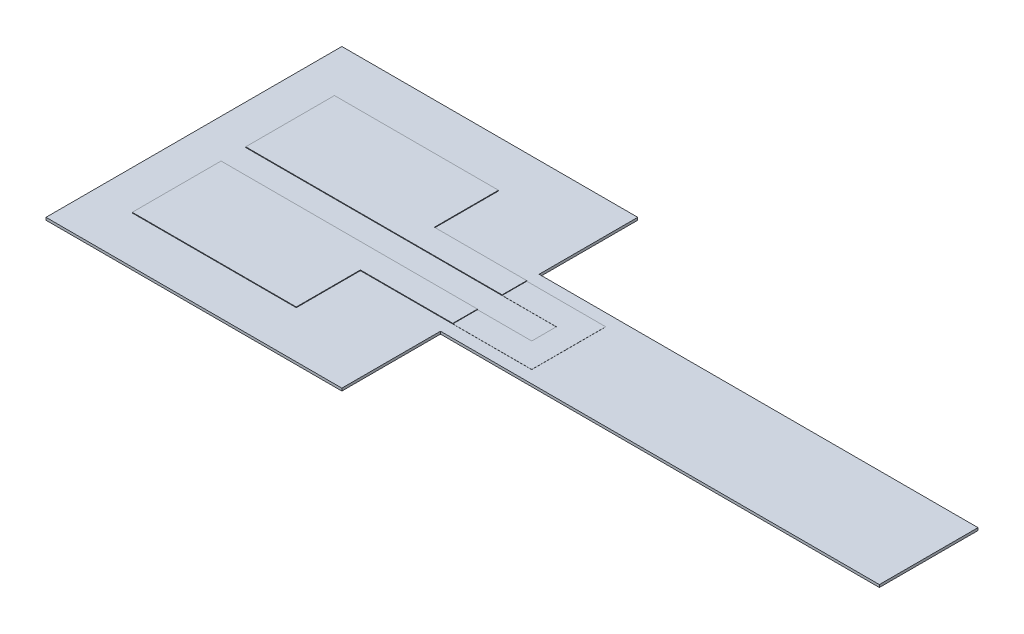
SolidWorks part; units mm, degrees
ref_plane "Front Plane" through (0, 0, 0) normal (0, 0, 1) x (1, 0, 0)
ref_plane "Top Plane" through (0, 0, 0) normal (0, 1, 0) x (1, 0, 0)
ref_plane "Right Plane" through (0, 0, 0) normal (1, 0, 0) x (0, 0, -1)
sketch "Sketch1" plane through (0, 0, 0) normal (0, 1, 0) x (1, 0, 0)
  line L2 (0, -15) -> (30, -15)
  line L3 (30, -15) -> (30, -5)
  line L4 (30, -5) -> (74.5, -5)
  line L5 (74.5, 5) -> (74.5, -5)
  line L6 (0, 15) -> (30, 15)
  line L7 (30, 15) -> (30, 5)
  line L8 (30, 5) -> (74.5, 5)
  line L9 (0, 15) -> (0, -15)
  line L10 (0, 0) -> (74.5, 0) construction
  dimension "D1" = 30
  dimension "D2" = 30
  dimension "D3" = 30
  dimension "D4" = 10
  dimension "D5" = 10
  dimension "D6" = 44.5
  dimension "D7" = 5
extrude "Boss-Extrude1" add sketch "Sketch1" against normal blind 0.26 and the other way blind 0.0001
sketch "Sketch3" plane through (0, 0.0001, 0) normal (0, 1, 0) x (1, 0, 0)
  line L0 (30, 5) -> (30, -5) construction
  line L1 (74.5, 0) -> (30, 0) construction
  line L2 (74.5, -5) -> (74.5, 5) construction
  line L3 (30, 3.75) -> (30, 1.25)
  line L4 (30, 1.25) -> (35.5, 1.25)
  line L5 (35.5, 1.25) -> (35.5, -1.25)
  line L6 (35.5, -1.25) -> (30, -1.25)
  line L7 (30, -1.25) -> (30, -3.75)
  line L8 (30, -3.75) -> (38, -3.75)
  line L9 (38, -3.75) -> (38, 3.75)
  line L10 (38, 3.75) -> (30, 3.75)
  dimension "D1" = 7.5
  dimension "D2" = 8
  dimension "D3" = 2.5
  dimension "D4" = 2.5
  dimension "D5" = 1.25
  dimension "D6" = 2.5
extrude "Boss-Extrude2" add sketch "Sketch3" along normal blind 0.0126 contours L10 L3 L4 L5 L6 L7 L8 L9
sketch "Sketch4" plane through (0, 0.0001, 0) normal (0, 1, 0) x (1, 0, 0)
  line L0 (4, 10.25) -> (4, 1.25)
  line L1 (30, 3.75) -> (20.6276, 3.75)
  line L2 (4, 10.25) -> (20.6276, 10.25)
  line L3 (20.6276, 10.25) -> (20.6276, 3.75)
  line L4 (30, 1.25) -> (4, 1.25)
  line L5 (30, 3.75) -> (30, 1.25)
  line L6 (30, -1.25) -> (4, -1.25)
  line L7 (30, -1.25) -> (30, -3.75)
  line L8 (30, -3.75) -> (20.6276, -3.75)
  line L9 (20.6276, -3.75) -> (20.6276, -10.25)
  line L10 (20.6276, -10.25) -> (4, -10.25)
  line L11 (4, -10.25) -> (4, -1.25)
  dimension "D1" = 6.5
  dimension "D2" = 6.5
  dimension "D3" = 26
  dimension "D4" = 26
extrude "Boss-Extrude3" add sketch "Sketch4" along normal blind 0.0666
